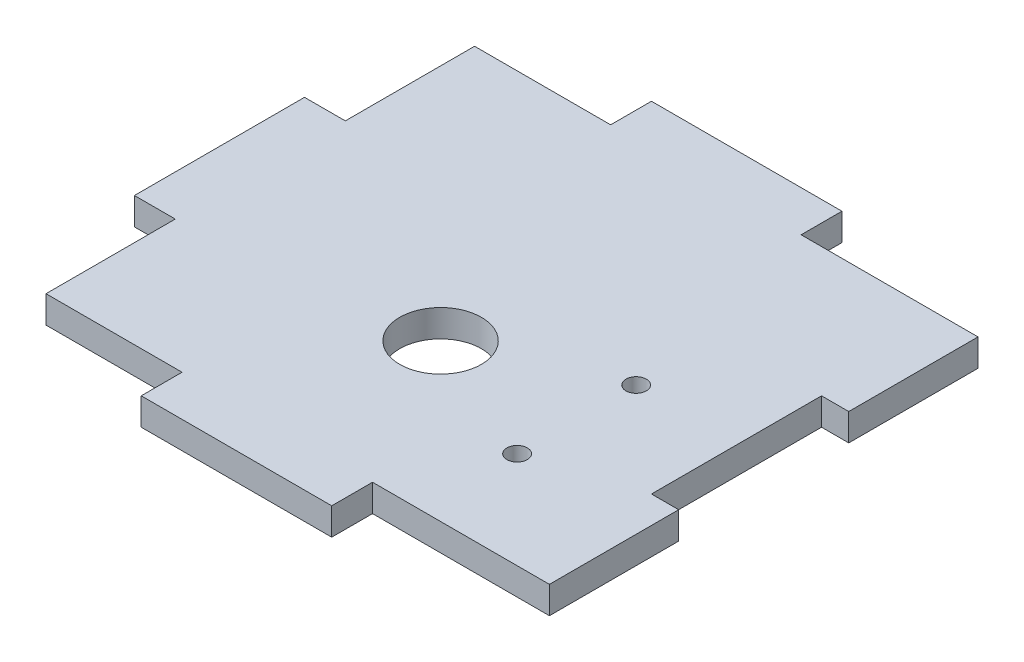
SolidWorks part; units mm, degrees
ref_plane "Front" through (0, 0, 0) normal (0, 0, 1) x (1, 0, 0)
ref_plane "Top" through (0, 0, 0) normal (0, 1, 0) x (1, 0, 0)
ref_plane "Right" through (0, 0, 0) normal (1, 0, 0) x (0, 0, -1)
sketch "Sketch1" plane through (0, 0, 0) normal (0, 1, 0) x (1, 0, 0)
  line L1 (0, 0) -> (80, 0)
  line L2 (0, 0) -> (0, 75)
  line L3 (0, 75) -> (80, 75)
  line L4 (80, 0) -> (80, 75)
  dimension "D1" = 80
  dimension "D2" = 75
extrude "Boss-Extrude1" add sketch "Sketch1" along normal blind 4
sketch "Sketch2" plane through (0, 4, 0) normal (0, 1, 0) x (1, 0, 0)
  line L0 (0, 0) -> (80, 0) construction
  line L1 (0, 75) -> (0, 0) construction
  circle A0 centre (41, 29) radius 6
  circle A1 centre (61, 37.75) radius 1.5
  circle A2 centre (61, 20.25) radius 1.5
  dimension "D3" = 12
  dimension "D4" = 3
  dimension "D1" = 29
  dimension "D2" = 41
  dimension "D5" = 17.5
  dimension "D6" = 20
  dimension "D7" = 8.75
extrude "Cut-Extrude1" cut sketch "Sketch2" against normal through all
sketch "Sketch3" plane through (0, 4, 0) normal (0, 1, 0) x (1, 0, 0)
  line L0 (80, 75) -> (0, 75) construction
  line L1 (80, 0) -> (76, 0)
  line L2 (80, 0) -> (80, 25)
  line L3 (80, 25) -> (76, 25)
  line L4 (76, 0) -> (76, 25)
  line L5 (80, 25) -> (76, 25)
  line L6 (80, 25) -> (80, 50)
  line L7 (80, 50) -> (76, 50)
  line L8 (76, 25) -> (76, 50)
  line L9 (80, 50) -> (76, 50)
  line L10 (80, 50) -> (80, 75)
  line L11 (80, 75) -> (76, 75)
  line L12 (76, 50) -> (76, 75)
  line L13 (0, 0) -> (80, 0) construction
  line L14 (0, 75) -> (6, 75)
  line L15 (0, 75) -> (0, 50)
  line L16 (0, 50) -> (6, 50)
  line L17 (6, 75) -> (6, 50)
  line L18 (0, 50) -> (6, 50)
  line L19 (0, 50) -> (0, 25)
  line L20 (0, 25) -> (6, 25)
  line L21 (6, 50) -> (6, 25)
  line L22 (0, 25) -> (6, 25)
  line L23 (0, 25) -> (0, 0)
  line L24 (0, 0) -> (6, 0)
  line L25 (6, 25) -> (6, 0)
  line L27 (0, 75) -> (26, 75)
  line L28 (0, 75) -> (0, 69)
  line L29 (0, 69) -> (26, 69)
  line L30 (26, 75) -> (26, 69)
  line L31 (80, 75) -> (54, 75)
  line L32 (80, 75) -> (80, 69)
  line L33 (80, 69) -> (54, 69)
  line L34 (54, 75) -> (54, 69)
  line L35 (0, 0) -> (26, 0)
  line L36 (0, 0) -> (0, 6)
  line L37 (0, 6) -> (26, 6)
  line L38 (26, 0) -> (26, 6)
  line L39 (80, 0) -> (54, 0)
  line L40 (80, 0) -> (80, 6)
  line L41 (80, 6) -> (54, 6)
  line L42 (54, 0) -> (54, 6)
  line M15 (0, 75) -> (0, 0)
  line M16 (0, 0) -> (80, 0)
  line M17 (80, 0) -> (80, 75)
  line M18 (80, 75) -> (0, 75)
  dimension "D1" = 6
  dimension "D2" = 4
  dimension "D3" = 6
  dimension "D4" = 26
  dimension "D5" = 6
extrude "Cut-Extrude2" cut sketch "Sketch3" against normal through all contours L8 L3 L7 M17 | L17 L16 M18 M15 | L25 L20 M15 M16 | L28 L27 L30 L29 | L32 L31 L34 L33 | L40 L39 L42 L41 | L36 L35 L38 L37
